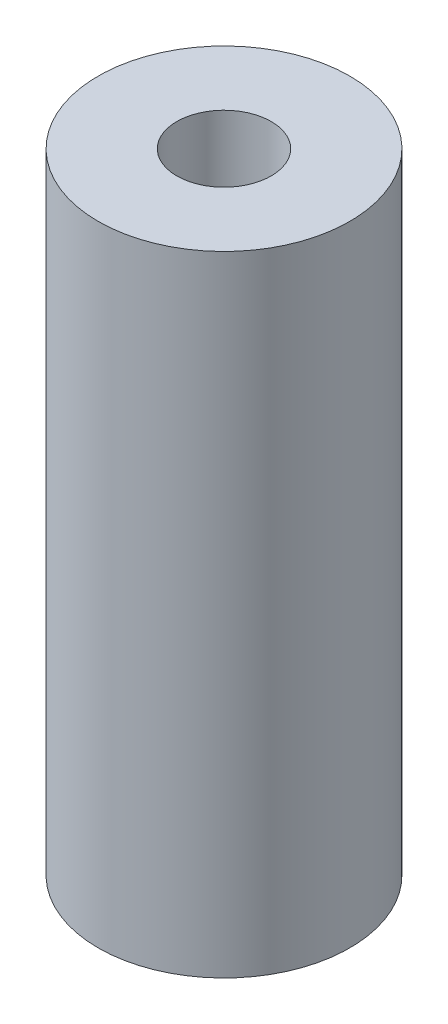
SolidWorks part; units mm, degrees
ref_plane "Front Plane" through (0, 0, 0) normal (0, 0, 1) x (1, 0, 0)
ref_plane "Top Plane" through (0, 0, 0) normal (0, 1, 0) x (1, 0, 0)
ref_plane "Right Plane" through (0, 0, 0) normal (1, 0, 0) x (0, 0, -1)
sketch "Sketch1" plane through (0, 0, 0) normal (0, 1, 0) x (1, 0, 0)
  circle A0 centre (0, 0) radius 4
  dimension "D1" = 8
extrude "Boss-Extrude1" add sketch "Sketch1" along normal blind 20
sketch "Sketch2" plane through (0, 20, 0) normal (0, 1, 0) x (1, 0, 0)
  circle A0 centre (0, 0) radius 1.5
  dimension "D1" = 3
extrude "Cut-Extrude1" cut sketch "Sketch2" against normal blind 15
